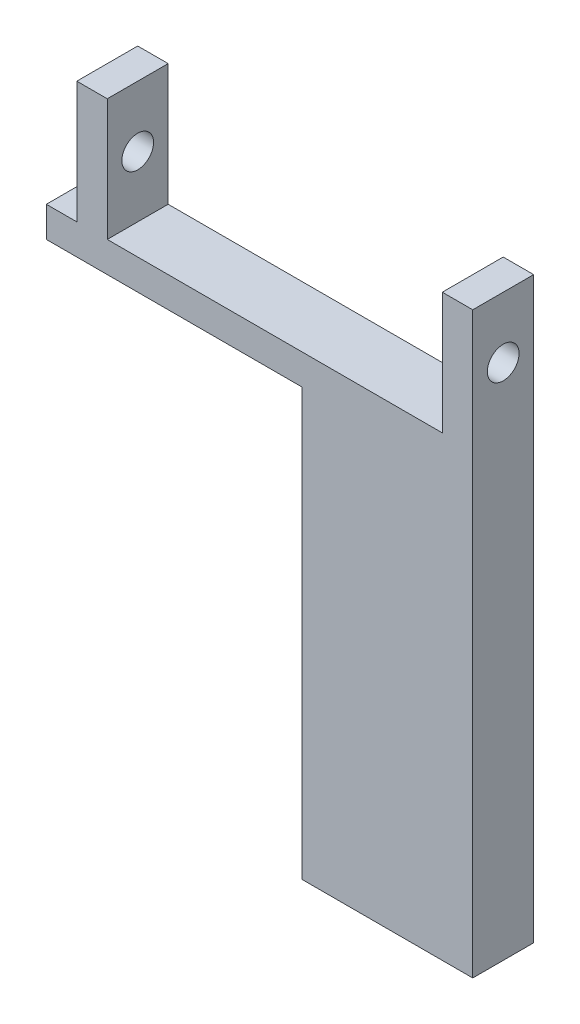
SolidWorks part; units mm, degrees
ref_plane "正面" through (0, 0, 0) normal (0, 0, 1) x (1, 0, 0)
ref_plane "平面" through (0, 0, 0) normal (0, 1, 0) x (1, 0, 0)
ref_plane "右側面" through (0, 0, 0) normal (1, 0, 0) x (0, 0, -1)
sketch "ｽｹｯﾁ2" plane through (0, 0, 0) normal (0, 0, 1) x (1, 0, 0)
  line L0 (-60, 75) -> (-5, 75)
  line L1 (-70, 75) -> (-65, 75)
  line L2 (-70, 75) -> (-70, 70)
  line L3 (-70, 70) -> (-28, 70)
  line L4 (0, 75) -> (0, 70)
  line L6 (-28, 70) -> (-28, 0)
  line L7 (-28, 0) -> (0, 0)
  line L8 (0, 70) -> (0, 0)
  line L10 (-65, 75) -> (-65, 95)
  line L11 (-65, 95) -> (-60, 95)
  line L12 (-60, 75) -> (-60, 95)
  line L14 (-5, 75) -> (-5, 95)
  line L15 (-5, 95) -> (0, 95)
  line L16 (0, 75) -> (0, 95)
  point P14 (0, 74.7922)
  point P15 (0, 75.461)
  point P17 (0, 0)
  dimension "D1" = 70
  dimension "D2" = 70
  dimension "D3" = 42
  dimension "D4" = 5
  dimension "D5" = 5
  dimension "D6" = 5
  dimension "D7" = 55
  dimension "D8" = 28
  dimension "D9" = 20
extrude "ﾎﾞｽ - 押し出し1" add sketch "ｽｹｯﾁ2" along normal blind 10
sketch "ｽｹｯﾁ3" plane through (-65, 0, 0) normal (-1, 0, 0) x (0, 0, 1)
  line L0 (10, 75) -> (0, 75) construction
  line L1 (10, 95) -> (10, 75) construction
  circle A0 centre (5, 85) radius 2.6
  dimension "D1" = 5.2
  dimension "D2" = 10
  dimension "D3" = 5
extrude "ｶｯﾄ - 押し出し1" cut sketch "ｽｹｯﾁ3" against normal through all
